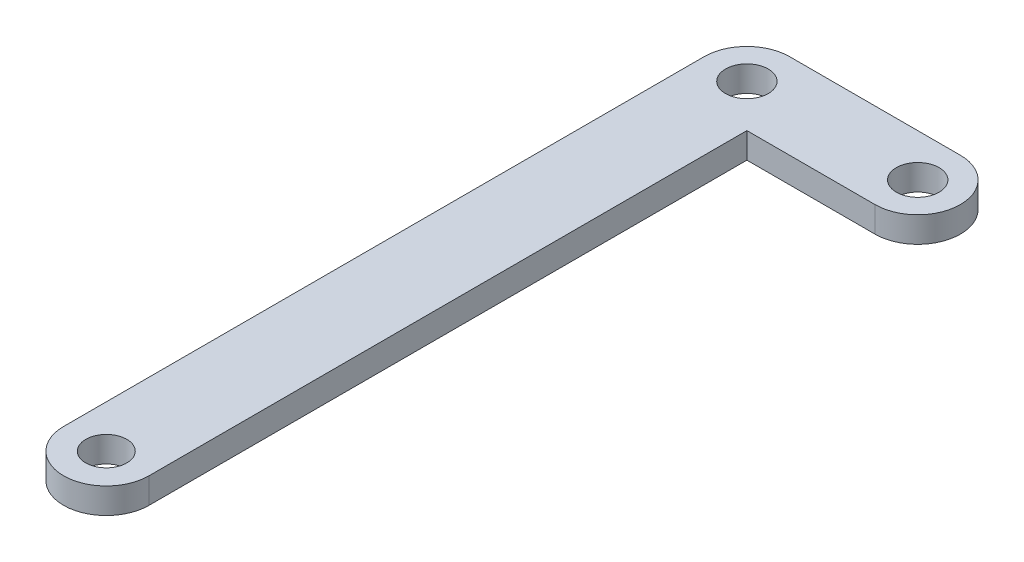
SolidWorks part; units mm, degrees
ref_plane "Front Plane" through (0, 0, 0) normal (0, 0, 1) x (1, 0, 0)
ref_plane "Top Plane" through (0, 0, 0) normal (0, 1, 0) x (1, 0, 0)
ref_plane "Right Plane" through (0, 0, 0) normal (1, 0, 0) x (0, 0, -1)
sketch "Sketch1" plane through (0, 0, 0) normal (0, 1, 0) x (1, 0, 0)
  line L7 (19.0688, -48.4258) -> (19.0688, 26.5742)
  line L8 (19.0688, 26.5742) -> (29.0688, 26.5742)
  line L9 (29.0688, -48.4258) -> (29.0688, 26.5742)
  line L10 (24.0688, 31.5742) -> (44.0688, 31.5742)
  line L11 (24.0688, 31.5742) -> (24.0688, 21.5742)
  line L12 (24.0688, 21.5742) -> (44.0688, 21.5742)
  arc A5 (19.0688, -48.4258) -> (29.0688, -48.4258) centre (24.0688, -48.4258) ccw
  circle A6 centre (24.0688, -48.4258) radius 2.4
  arc A7 (44.0688, 31.5742) -> (44.0688, 21.5742) centre (44.0688, 26.5742) cw
  circle A8 centre (44.0688, 26.5742) radius 2.5
  arc A9 (24.0688, 31.5742) -> (19.0688, 26.5742) centre (24.0688, 26.5742) ccw
  circle A10 centre (24.0688, 26.5742) radius 2.5
  point P17 (29.0688, 21.5742)
  point P24 (29.0688, 21.5742)
  dimension "D4" = 75
  dimension "D7" = 4.8
  dimension "D11" = 5
  dimension "D13" = 5
  dimension "D6" = 10
  dimension "D8" = 70
  dimension "D9" = 20
  dimension "D10" = 10
  dimension "D12" = 15
extrude "Boss-Extrude1" add sketch "Sketch1" along normal blind 3 contours A10 L8 L7 A5 L9 L12 L11 A6 | A10 L8 L9 L12 A7 L10 L11 A8 | A10 L11 L12 L9 L8 | A10 L11 A9 L8
